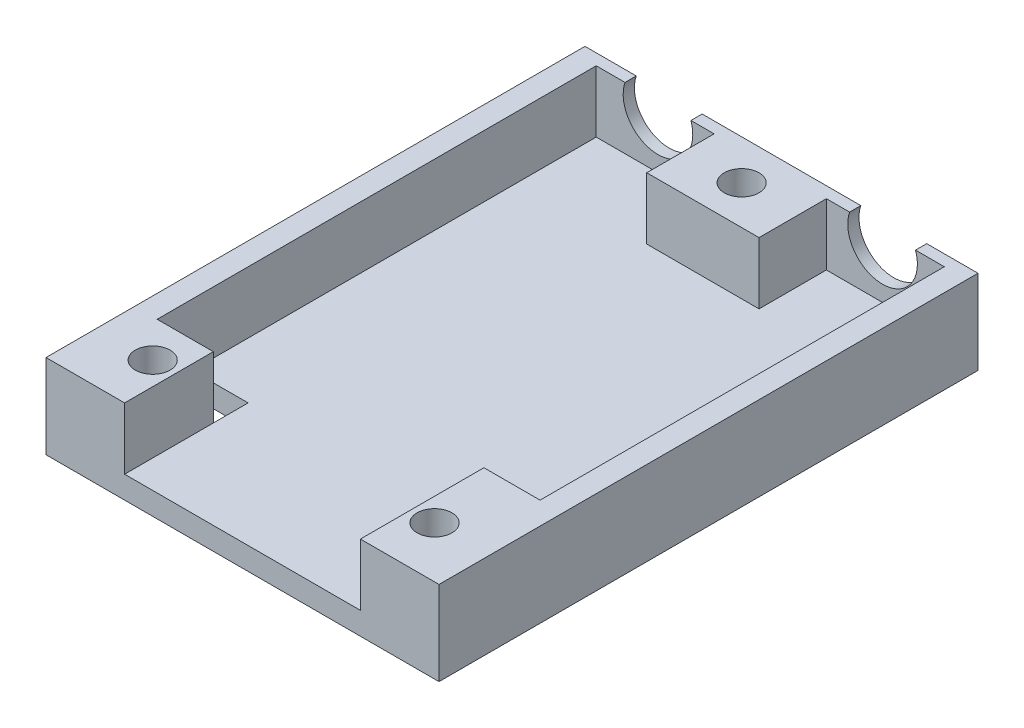
SolidWorks part; units mm, degrees
ref_plane "Front Plane" through (0, 0, 0) normal (0, 0, 1) x (1, 0, 0)
ref_plane "Top Plane" through (0, 0, 0) normal (0, 1, 0) x (1, 0, 0)
ref_plane "Right Plane" through (0, 0, 0) normal (1, 0, 0) x (0, 0, -1)
sketch "Sketch1" plane through (0, 0, 0) normal (0, 1, 0) x (1, 0, 0)
  line L1 (-17.5, 24) -> (17.5, 24)
  line L2 (-17.5, 24) -> (-17.5, -24)
  line L3 (-17.5, -24) -> (17.5, -24)
  line L4 (17.5, 24) -> (17.5, -24)
  line L5 (-44.2539, 0) -> (44.2539, 0) construction
  line L6 (0, -44.7868) -> (0, 44.7868) construction
  dimension "D2" = 35
  dimension "D1" = 48
  dimension "D3" = 24
  dimension "D4" = 17.5
extrude "Boss-Extrude1" add sketch "Sketch1" along normal blind 2
sketch "Sketch2" plane through (0, 2, 0) normal (0, 1, 0) x (1, 0, 0)
  line L1 (-15.5, 23) -> (15.5, 23)
  line L2 (-15.5, 23) -> (-15.5, -21)
  line L3 (-15.5, -21) -> (15.5, -21)
  line L4 (15.5, 23) -> (15.5, -21)
  line L6 (17.5, -24) -> (17.5, 24) construction
  line L7 (-17.5, -24) -> (17.5, -24) construction
  line M5 (-17.5, 24) -> (-17.5, -24)
  line M6 (-17.5, -24) -> (17.5, -24)
  line M7 (17.5, -24) -> (17.5, 24)
  line M8 (17.5, 24) -> (-17.5, 24)
  dimension "D1" = 2
  dimension "D2" = 3
  dimension "D3" = 31
  dimension "D4" = 44
extrude "Boss-Extrude2" add sketch "Sketch2" along normal blind 5.5 contours L1 L4 L3 L2 M8 M5 M6 M7
sketch "Sketch3" plane through (0, 2, 0) normal (0, 1, 0) x (1, 0, 0)
  line L0 (-15.5, 23) -> (15.5, 23) construction
  line L1 (-5, 23) -> (5, 23)
  line L2 (-5, 23) -> (-5, 17)
  line L3 (-5, 17) -> (5, 17)
  line L4 (5, 23) -> (5, 17)
  line L5 (15.5, 23) -> (15.5, -21) construction
  line L7 (-15.5, -21) -> (-10.5, -21)
  line L8 (-15.5, -21) -> (-15.5, -13)
  line L9 (-15.5, -13) -> (-10.5, -13)
  line L10 (-10.5, -21) -> (-10.5, -13)
  line L11 (15.5, -21) -> (10.5, -21)
  line L12 (15.5, -21) -> (15.5, -13)
  line L13 (15.5, -13) -> (10.5, -13)
  line L14 (10.5, -21) -> (10.5, -13)
  dimension "D1" = 10
  dimension "D2" = 6
  dimension "D3" = 10.5
  dimension "D4" = 5
  dimension "D5" = 5
  dimension "D6" = 8
  dimension "D7" = 8
extrude "Boss-Extrude3" add sketch "Sketch3" along normal blind 5.5
sketch "Sketch4" plane through (0, 0, 24) normal (0, 0, 1) x (1, 0, 0)
  line L0 (-17.5, 7.5) -> (17.5, 7.5) construction
  line L1 (-10.5, 7.5) -> (10.5, 7.5)
  line L2 (-10.5, 7.5) -> (-10.5, 2)
  line L3 (-10.5, 2) -> (10.5, 2)
  line L4 (10.5, 7.5) -> (10.5, 2)
  line L5 (-17.5, 7.5) -> (-17.5, 0) construction
  line L6 (17.5, 7.5) -> (17.5, 0) construction
  dimension "D1" = 7
  dimension "D2" = 7
  dimension "D3" = 5.5
extrude "Cut-Extrude1" cut sketch "Sketch4" against normal up to surface (3 mm away) up to face at (0, 4.75, 21)
sketch "Sketch5" plane through (0, 0, 0) normal (0, -1, 0) x (1, 0, 0)
  line L0 (44.2539, 0) -> (-44.2539, 0) construction
  line L1 (-2.45, 8.5) -> (2.45, 8.5)
  line L2 (-2.45, 8.5) -> (-2.45, 3.6)
  line L3 (-2.45, 3.6) -> (2.45, 3.6)
  line L4 (2.45, 8.5) -> (2.45, 3.6)
  line L5 (-2.45, -3.6) -> (2.45, -3.6)
  line L6 (-2.45, -3.6) -> (-2.45, -8.5)
  line L7 (-2.45, -8.5) -> (2.45, -8.5)
  line L8 (2.45, -3.6) -> (2.45, -8.5)
  line L9 (17.5, 24) -> (17.5, -24) construction
  dimension "D1" = 4.9
  dimension "D2" = 7.2
  dimension "D3" = 3.6
  dimension "D4" = 15.05
  dimension "D5" = 15.05
extrude "Boss-Extrude4" add sketch "Sketch5" along normal blind 2
sketch "Sketch6" plane through (0, 0, -24) normal (0, 0, -1) x (-1, 0, 0)
  line L0 (-17.5, 7.5) -> (17.5, 7.5) construction
  line L3 (-17.5, 7.5) -> (-17.5, 0) construction
  arc A0 (-7.0657, 7.5) -> (-12.9343, 7.5) centre (-10, 6.5) cw
  arc A1 (12.9343, 7.5) -> (7.0657, 7.5) centre (10, 6.5) cw
  line M3 (17.5, 7.5) -> (-17.5, 7.5)
  dimension "D1" = 20
  dimension "D3" = 3.1
  dimension "D4" = 3.1
  dimension "D2" = 7.5
  dimension "D5" = 1
  dimension "D6" = 1
extrude "Cut-Extrude2" cut sketch "Sketch6" against normal blind 2 contours A0 M3 | A1 M3
sketch "Sketch7" plane through (0, 7.5, 0) normal (0, 1, 0) x (1, 0, 0)
  line L0 (-10.5, -13) -> (-15.5, -13) construction
  line L1 (-15.5, -13) -> (-10.5, -13)
  line L2 (-15.5, -13) -> (-15.5, -16.1)
  line L3 (-15.5, -16.1) -> (-10.5, -16.1)
  line L4 (-10.5, -13) -> (-10.5, -16.1)
  line L5 (-10.5, -24) -> (-10.5, -13) construction
  dimension "D1" = 3.1
  dimension "D2" = 5
extrude "Cut-Extrude3" cut sketch "Sketch7" against normal up to surface (7.5 mm away)
sketch "Sketch8" plane through (0, 0, 0) normal (0, 1, 0) x (1, 0, 0)
  line L0 (0, -44.7868) -> (0, 44.7868) construction
  line L1 (10.5, -24) -> (17.5, -24) construction
  line L4 (-17.5, -24) -> (-10.5, -24) construction
  line L6 (-15.5, 23) -> (-5, 23) construction
  circle A0 centre (-12.55, -19.45) radius 1.55
  circle A1 centre (12.55, -19.45) radius 1.55
  circle A2 centre (0, 20.45) radius 1.55
  dimension "D1" = 3.1
  dimension "D7" = 3.1
  dimension "D8" = 3.1
  dimension "D2" = 4.55
  dimension "D3" = 25.1
  dimension "D4" = 4.55
  dimension "D5" = 12.55
  dimension "D6" = 2.55
extrude "Cut-Extrude4" cut sketch "Sketch8" along direction (0, 1, 0) on the side against the normal blind 5.5 from surface at 7.5 starting at face at (-14.1086, 7.5, -1.725)
equation "\"fWidth\"=35"
equation "\"D2@Sketch1\"=\"fWidth\""
equation "\"fLength\"= 48"
equation "\"D1@Sketch1\"=\"fLength\""
equation "\"D3@Sketch1\"=\"fLength\"/2"
equation "\"D4@Sketch1\"=\"fWidth\"/2"
equation "\"wThickness\"=2"
equation "\"D1@Sketch2\"=\"wThickness\""
equation "\"D3@Sketch2\"=\"fWidth\"- 2* \"wThickness\""
equation "\"D4@Sketch2\"=\"fLength\"- 2 *\"wThickness\""
equation "\"wHeight\"= 5.5"
equation "\"D1@Boss-Extrude2\"=\"wHeight\""
equation "\"D3@Sketch3\"=(\"fWidth\"- 2 *\"wThickness\" - 10)/2"
equation "\"D4@Sketch5\"=(\"fWidth\"- 4.9)/2"
equation "\"D5@Sketch5\"=(\"fWidth\"- 4.9)/2"
equation "\"D3@Sketch4\"=\"wHeight\""
